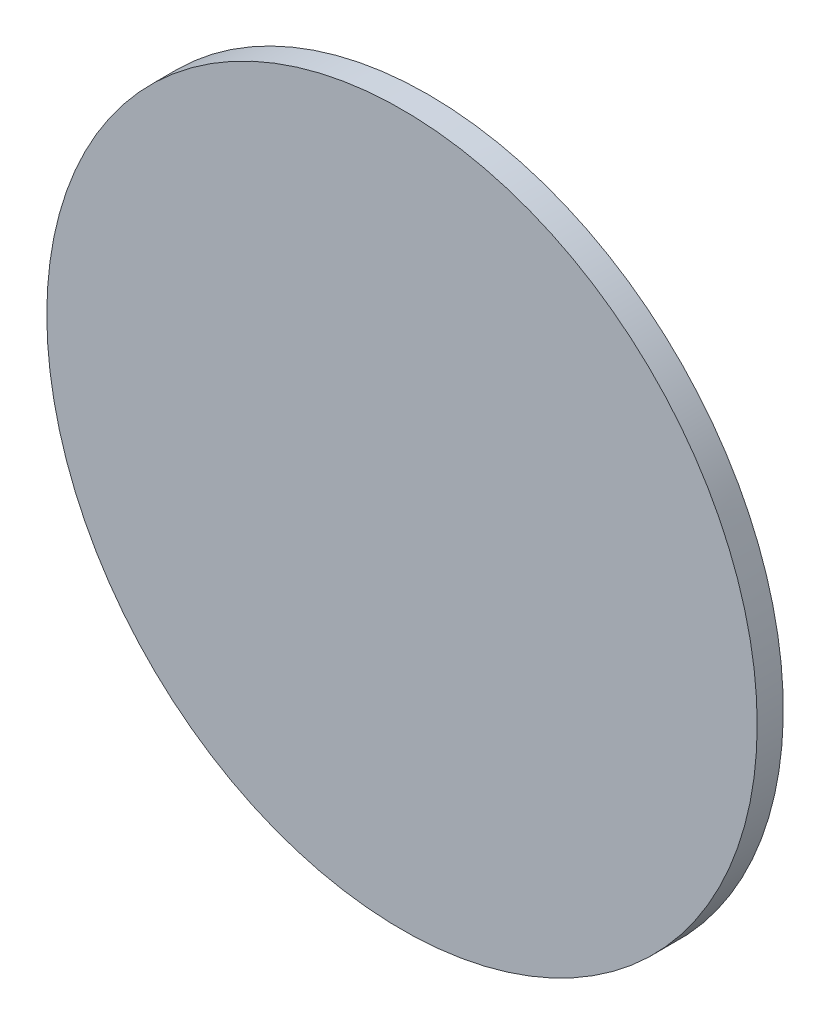
SolidWorks part; units mm, degrees
ref_plane "前视基准面" through (0, 0, 0) normal (0, 0, 1) x (1, 0, 0)
ref_plane "上视基准面" through (0, 0, 0) normal (0, 1, 0) x (1, 0, 0)
ref_plane "右视基准面" through (0, 0, 0) normal (1, 0, 0) x (0, 0, -1)
other "Configuration Table"
curve "曲线20"
  spline degree 3 poles (0, 0, 0) (0, 0.0067, 0.0001) (0, 0.02, 0.0004) (0, 0.04, 0.0008) (0, 0.06, 0.0012) (0, 0.08, 0.0016) (0, 0.1, 0.002) (0, 0.12, 0.0024) (0, 0.14, 0.0028) (0, 0.16, 0.0032) (0, 0.18, 0.0036) (0, 0.2, 0.004) (0, 0.22, 0.0044) (0, 0.24, 0.0048) (0, 0.26, 0.0052) (0, 0.28, 0.0056) (0, 0.3, 0.006) (0, 0.32, 0.0064) (0, 0.34, 0.0068) (0, 0.36, 0.0072) (0, 0.38, 0.0076) (0, 0.4, 0.008) (0, 0.42, 0.0084) (0, 0.44, 0.0088) (0, 0.46, 0.0092) (0, 0.48, 0.0096) (0, 0.5, 0.01) (0, 0.52, 0.0104) (0, 0.54, 0.0108) (0, 0.56, 0.0112) (0, 0.58, 0.0116) (0, 0.6, 0.012) (0, 0.62, 0.0124) (0, 0.64, 0.0128) (0, 0.66, 0.0132) (0, 0.68, 0.0136) (0, 0.7, 0.014) (0, 0.72, 0.0144) (0, 0.74, 0.0148) (0, 0.76, 0.0152) (0, 0.78, 0.0156) (0, 0.8, 0.016) (0, 0.82, 0.0164) (0, 0.84, 0.0168) (0, 0.86, 0.0172) (0, 0.88, 0.0176) (0, 0.9, 0.018) (0, 0.92, 0.0184) (0, 0.9399, 0.0187) (0, 0.9605, 0.0197) (0, 0.978, 0.0176) (0, 1.0024, 0.0258) (0, 1, 0.01) (0, 0.9976, -0.0059) (0, 1.022, 0.0033) (0, 1.0395, 0.0018) (0, 1.0601, 0.0038) (0, 1.08, 0.0048) (0, 1.1, 0.006) (0, 1.12, 0.0072) (0, 1.14, 0.0084) (0, 1.16, 0.0096) (0, 1.18, 0.0108) (0, 1.2, 0.012) (0, 1.22, 0.0132) (0, 1.24, 0.0144) (0, 1.26, 0.0156) (0, 1.28, 0.0168) (0, 1.3, 0.018) (0, 1.32, 0.0192) (0, 1.34, 0.0204) (0, 1.36, 0.0216) (0, 1.38, 0.0228) (0, 1.4, 0.024) (0, 1.42, 0.0253) (0, 1.44, 0.0265) (0, 1.46, 0.0277) (0, 1.48, 0.0289) (0, 1.5, 0.0301) (0, 1.52, 0.0313) (0, 1.54, 0.0325) (0, 1.56, 0.0337) (0, 1.58, 0.0349) (0, 1.6, 0.0361) (0, 1.62, 0.0373) (0, 1.64, 0.0385) (0, 1.66, 0.0397) (0, 1.68, 0.0409) (0, 1.7, 0.0421) (0, 1.72, 0.0433) (0, 1.74, 0.0445) (0, 1.76, 0.0457) (0, 1.78, 0.0469) (0, 1.8, 0.0481) (0, 1.82, 0.0493) (0, 1.84, 0.0505) (0, 1.86, 0.0517) (0, 1.88, 0.0529) (0, 1.9, 0.0541) (0, 1.92, 0.0553) (0, 1.9399, 0.0564) (0, 1.9604, 0.0582) (0, 1.9784, 0.0572) (0, 2.0059, 0.0664) (0, 1.998, 0.038) (0, 2.002, 0.0222) (0, 1.9941, -0.0065) (0, 2.0216, 0.0038) (0, 2.0396, 0.0036) (0, 2.0601, 0.0062) (0, 2.08, 0.008) (0, 2.1, 0.0101) (0, 2.12, 0.0121) (0, 2.14, 0.0141) (0, 2.16, 0.0161) (0, 2.18, 0.0181) (0, 2.2, 0.0201) (0, 2.22, 0.0221) (0, 2.24, 0.0241) (0, 2.26, 0.0261) (0, 2.28, 0.0281) (0, 2.3, 0.0302) (0, 2.32, 0.0322) (0, 2.34, 0.0342) (0, 2.36, 0.0362) (0, 2.38, 0.0382) (0, 2.4, 0.0402) (0, 2.42, 0.0422) (0, 2.44, 0.0442) (0, 2.46, 0.0462) (0, 2.48, 0.0483) (0, 2.5, 0.0503) (0, 2.52, 0.0523) (0, 2.54, 0.0543) (0, 2.56, 0.0563) (0, 2.58, 0.0583) (0, 2.6, 0.0603) (0, 2.62, 0.0623) (0, 2.64, 0.0643) (0, 2.66, 0.0663) (0, 2.68, 0.0684) (0, 2.7, 0.0704) (0, 2.72, 0.0724) (0, 2.74, 0.0744) (0, 2.76, 0.0764) (0, 2.78, 0.0784) (0, 2.8, 0.0804) (0, 2.82, 0.0824) (0, 2.84, 0.0844) (0, 2.86, 0.0865) (0, 2.88, 0.0885) (0, 2.9, 0.0905) (0, 2.92, 0.0925) (0, 2.9399, 0.0944) (0, 2.9604, 0.097) (0, 2.9785, 0.0968) (0, 3.0058, 0.1069) (0, 2.9984, 0.0787) (0, 3.0005, 0.0609) (0, 2.9995, 0.0396) (0, 3.0016, 0.0219) (0, 2.9942, -0.0067) (0, 3.0216, 0.0046) (0, 3.0396, 0.0052) (0, 3.0601, 0.0086) (0, 3.08, 0.0113) (0, 3.1, 0.0142) (0, 3.12, 0.017) (0, 3.14, 0.0198) (0, 3.16, 0.0226) (0, 3.18, 0.0255) (0, 3.2, 0.0283) (0, 3.22, 0.0311) (0, 3.24, 0.0339) (0, 3.26, 0.0368) (0, 3.28, 0.0396) (0, 3.3, 0.0424) (0, 3.32, 0.0453) (0, 3.34, 0.0481) (0, 3.36, 0.0509) (0, 3.38, 0.0537) (0, 3.4, 0.0566) (0, 3.42, 0.0594) (0, 3.44, 0.0622) (0, 3.46, 0.0651) (0, 3.48, 0.0679) (0, 3.5, 0.0707) (0, 3.52, 0.0735) (0, 3.54, 0.0764) (0, 3.56, 0.0792) (0, 3.58, 0.082) (0, 3.6, 0.0849) (0, 3.62, 0.0877) (0, 3.64, 0.0905) (0, 3.66, 0.0933) (0, 3.68, 0.0962) (0, 3.7, 0.099) (0, 3.72, 0.1018) (0, 3.74, 0.1047) (0, 3.76, 0.1075) (0, 3.78, 0.1103) (0, 3.8, 0.1131) (0, 3.82, 0.116) (0, 3.84, 0.1188) (0, 3.86, 0.1216) (0, 3.88, 0.1245) (0, 3.9, 0.1273) (0, 3.92, 0.1301) (0, 3.9399, 0.1328) (0, 3.9604, 0.1362) (0, 3.9785, 0.1368) (0, 4.0058, 0.1481) (0, 3.9985, 0.1194) (0, 4.0004, 0.1015) (0, 3.9999, 0.0806) (0, 4.0001, 0.0608) (0, 3.9996, 0.0399) (0, 4.0015, 0.022) (0, 3.9943, -0.0069) (0, 4.0216, 0.0055) (0, 4.0396, 0.0068) (0, 4.0601, 0.0111) (0, 4.08, 0.0146) (0, 4.1, 0.0183) (0, 4.12, 0.022) (0, 4.14, 0.0256) (0, 4.16, 0.0293) (0, 4.18, 0.0329) (0, 4.2, 0.0366) (0, 4.22, 0.0403) (0, 4.24, 0.0439) (0, 4.26, 0.0476) (0, 4.28, 0.0512) (0, 4.3, 0.0549) (0, 4.32, 0.0586) (0, 4.34, 0.0622) (0, 4.36, 0.0659) (0, 4.38, 0.0696) (0, 4.4, 0.0732) (0, 4.42, 0.0769) (0, 4.44, 0.0805) (0, 4.46, 0.0842) (0, 4.48, 0.0879) (0, 4.5, 0.0915) (0, 4.52, 0.0952) (0, 4.54, 0.0988) (0, 4.56, 0.1025) (0, 4.58, 0.1062) (0, 4.6, 0.1098) (0, 4.62, 0.1135) (0, 4.64, 0.1171) (0, 4.66, 0.1208) (0, 4.68, 0.1245) (0, 4.7, 0.1281) (0, 4.72, 0.1318) (0, 4.74, 0.1354) (0, 4.76, 0.1391) (0, 4.78, 0.1428) (0, 4.8, 0.1464) (0, 4.82, 0.1501) (0, 4.84, 0.1537) (0, 4.86, 0.1574) (0, 4.88, 0.1611) (0, 4.9, 0.1647) (0, 4.92, 0.1684) (0, 4.94, 0.172) (0, 4.96, 0.1757) (0, 4.98, 0.1794) (0, 4.9933, 0.1818) (0, 5, 0.183) knots 0 0 0 0 0.003735 0.00747 0.011205 0.01494 0.018675 0.022411 0.026146 0.029881 0.033616 0.037351 0.041086 0.044821 0.048556 0.052291 0.056026 0.059762 0.063497 0.067232 0.070967 0.074702 0.078437 0.082172 0.085907 0.089642 0.093377 0.097113 0.100848 0.104583 0.108318 0.112053 0.115788 0.119523 0.123258 0.126993 0.130728 0.134464 0.138199 0.141934 0.145669 0.149404 0.153139 0.156874 0.160609 0.164344 0.168079 0.171815 0.17555 0.179285 0.18302 0.186755 0.188623 0.190491 0.194232 0.197973 0.201714 0.205455 0.209196 0.212937 0.216678 0.22042 0.224161 0.227902 0.231643 0.235384 0.239125 0.242866 0.246607 0.250348 0.254089 0.257831 0.261572 0.265313 0.269054 0.272795 0.276536 0.280277 0.284018 0.287759 0.2915 0.295241 0.298983 0.302724 0.306465 0.310206 0.313947 0.317688 0.321429 0.32517 0.328911 0.332652 0.336393 0.340135 0.343876 0.347617 0.351358 0.355099 0.35884 0.362581 0.366322 0.370063 0.373804 0.377546 0.381287 0.385029 0.388771 0.392524 0.396277 0.40003 0.403784 0.407537 0.41129 0.415043 0.418796 0.42255 0.426303 0.430056 0.433809 0.437562 0.441315 0.445069 0.448822 0.452575 0.456328 0.460081 0.463834 0.467588 0.471341 0.475094 0.478847 0.4826 0.486353 0.490107 0.49386 0.497613 0.501366 0.505119 0.508873 0.512626 0.516379 0.520132 0.523885 0.527638 0.531392 0.535145 0.538898 0.542651 0.546404 0.550157 0.553911 0.557664 0.561417 0.56517 0.568923 0.572676 0.57643 0.580184 0.583937 0.587691 0.591445 0.595199 0.598971 0.602742 0.606514 0.610285 0.614057 0.617828 0.6216 0.625371 0.629143 0.632914 0.636686 0.640457 0.644229 0.648 0.651772 0.655543 0.659315 0.663086 0.666858 0.670629 0.674401 0.678172 0.681944 0.685715 0.689487 0.693258 0.69703 0.700802 0.704573 0.708345 0.712116 0.715888 0.719659 0.723431 0.727202 0.730974 0.734745 0.738517 0.742288 0.74606 0.749831 0.753603 0.757374 0.761146 0.764917 0.768689 0.77246 0.776232 0.780003 0.783775 0.787547 0.791319 0.795092 0.798864 0.802636 0.806408 0.810181 0.813977 0.817773 0.82157 0.825366 0.829163 0.832959 0.836755 0.840552 0.844348 0.848145 0.851941 0.855737 0.859534 0.86333 0.867126 0.870923 0.874719 0.878516 0.882312 0.886108 0.889905 0.893701 0.897498 0.901294 0.90509 0.908887 0.912683 0.91648 0.920276 0.924072 0.927869 0.931665 0.935461 0.939258 0.943054 0.946851 0.950647 0.954443 0.95824 0.962036 0.965833 0.969629 0.973425 0.977222 0.981018 0.984814 0.988611 0.992407 0.996204 1 1 1 1
sketch "草图2" plane through (0, 0, 0) normal (1, 0, 0) x (0, 0, -1)
  line L0 (0, 0) -> (-2.238, 0) construction
  line L2 (0, 0) -> (-0.5501, 0)
  line L3 (-0.5501, 0) -> (-0.5501, 5)
  line L4 (-0.5501, 5) -> (-0.183, 5)
  spline S0 degree 3 poles (1998.7905, -46.854) (0.6978, -57.8992) (0.5787, -28.9283) (-0.0048, 0.24) (-0.0099, 0.4933) (-0.0152, 0.76) (-0.0165, 0.8267) (-0.0172, 0.86) (-0.0176, 0.88) (-0.018, 0.9) (-0.0184, 0.92) (-0.0187, 0.9399) (-0.0197, 0.9605) (-0.0176, 0.978) (-0.0258, 1.0024) (-0.01, 1) (0.0059, 0.9976) (-0.0033, 1.022) (-0.0018, 1.0395) (-0.0038, 1.0601) (-0.0048, 1.08) (-0.006, 1.1) (-0.0072, 1.12) (-0.0096, 1.16) (-0.0128, 1.2133) (-0.0172, 1.2867) (-0.0216, 1.36) (-0.0261, 1.4333) (-0.0305, 1.5067) (-0.0349, 1.58) (-0.0393, 1.6533) (-0.0437, 1.7267) (-0.0473, 1.7867) (-0.0501, 1.8333) (-0.0517, 1.86) (-0.0529, 1.88) (-0.0541, 1.9) (-0.0553, 1.92) (-0.0564, 1.9399) (-0.0582, 1.9604) (-0.0572, 1.9784) (-0.0664, 2.0059) (-0.038, 1.998) (-0.0222, 2.002) (0.0065, 1.9941) (-0.0038, 2.0216) (-0.0036, 2.0396) (-0.0062, 2.0601) (-0.008, 2.08) (-0.0101, 2.1) (-0.0127, 2.1267) (-0.0168, 2.1667) (-0.0221, 2.22) (-0.0282, 2.28) (-0.0342, 2.34) (-0.0402, 2.4) (-0.0462, 2.46) (-0.0523, 2.52) (-0.0583, 2.58) (-0.065, 2.6467) (-0.0717, 2.7133) (-0.0784, 2.78) (-0.0831, 2.8267) (-0.0865, 2.86) (-0.0885, 2.88) (-0.0905, 2.9) (-0.0925, 2.92) (-0.0944, 2.9399) (-0.097, 2.9604) (-0.0968, 2.9785) (-0.1069, 3.0058) (-0.0787, 2.9984) (-0.0609, 3.0005) (-0.0396, 2.9995) (-0.0219, 3.0016) (0.0067, 2.9942) (-0.0046, 3.0216) (-0.0052, 3.0396) (-0.0086, 3.0601) (-0.0113, 3.08) (-0.0142, 3.1) (-0.0179, 3.1267) (-0.0226, 3.16) (-0.0292, 3.2067) (-0.0377, 3.2667) (-0.0471, 3.3333) (-0.0566, 3.4) (-0.066, 3.4667) (-0.0754, 3.5333) (-0.0858, 3.6067) (-0.0952, 3.6733) (-0.1056, 3.7467) (-0.1141, 3.8067) (-0.1207, 3.8533) (-0.1245, 3.88) (-0.1273, 3.9) (-0.1301, 3.92) (-0.1328, 3.9399) (-0.1362, 3.9604) (-0.1368, 3.9785) (-0.1481, 4.0058) (-0.1194, 3.9985) (-0.1015, 4.0004) (-0.0806, 3.9999) (-0.0608, 4.0001) (-0.0399, 3.9996) (-0.022, 4.0015) (0.0069, 3.9943) (-0.0055, 4.0216) (-0.0068, 4.0396) (-0.0111, 4.0601) (-0.0146, 4.08) (-0.0183, 4.1) (-0.022, 4.12) (-0.0293, 4.16) (-0.039, 4.2133) (-0.0525, 4.2867) (-0.0647, 4.3533) (-0.0781, 4.4267) (-0.0903, 4.4933) (-0.1025, 4.56) (-0.1147, 4.6267) (-0.1269, 4.6933) (-0.1391, 4.76) (-0.1513, 4.8267) (-0.1635, 4.8933) (-0.1733, 4.9467) (-2.3397, 16.7879) (-5.6155, 28.4054) (1960.1782, 400.405) knots -16.21873 -16.21873 -16.21873 -16.21873 0.003735 0.00747 0.123258 0.145669 0.156874 0.160609 0.164344 0.168079 0.171815 0.17555 0.179285 0.18302 0.186755 0.188623 0.190491 0.194232 0.197973 0.201714 0.205455 0.209196 0.212937 0.216678 0.231643 0.242866 0.257831 0.272795 0.284018 0.298983 0.313947 0.32517 0.340135 0.347617 0.351358 0.355099 0.35884 0.362581 0.366322 0.370063 0.373804 0.377546 0.381287 0.385029 0.388771 0.392524 0.396277 0.40003 0.403784 0.407537 0.41129 0.418796 0.430056 0.441315 0.452575 0.463834 0.475094 0.486353 0.497613 0.508873 0.523885 0.535145 0.546404 0.550157 0.553911 0.557664 0.561417 0.56517 0.568923 0.572676 0.57643 0.580184 0.583937 0.587691 0.591445 0.595199 0.598971 0.602742 0.606514 0.610285 0.614057 0.617828 0.625371 0.632914 0.644229 0.659315 0.670629 0.681944 0.69703 0.708345 0.723431 0.734745 0.749831 0.757374 0.761146 0.764917 0.768689 0.77246 0.776232 0.780003 0.783775 0.787547 0.791319 0.795092 0.798864 0.802636 0.806408 0.810181 0.813977 0.817773 0.82157 0.825366 0.829163 0.832959 0.836755 0.851941 0.86333 0.878516 0.889905 0.90509 0.91648 0.927869 0.943054 0.954443 0.965833 0.981018 0.992407 0.996204 7.724012 7.724012 7.724012 7.724012 only from (0, 0) to (-0.183, 5) construction
  spline S1 degree 3 poles (0, 0) (-0.0012, 0.06) (-0.0031, 0.1533) (-0.0083, 0.4133) (-0.0127, 0.6333) (-0.0165, 0.8267) (-0.0172, 0.86) (-0.0176, 0.88) (-0.018, 0.9) (-0.0184, 0.92) (-0.0187, 0.9399) (-0.0197, 0.9605) (-0.0176, 0.978) (-0.0258, 1.0024) (-0.01, 1) (0.0059, 0.9976) (-0.0033, 1.022) (-0.0018, 1.0395) (-0.0038, 1.0601) (-0.0048, 1.08) (-0.006, 1.1) (-0.0072, 1.12) (-0.0096, 1.16) (-0.0128, 1.2133) (-0.0172, 1.2867) (-0.0216, 1.36) (-0.0261, 1.4333) (-0.0305, 1.5067) (-0.0349, 1.58) (-0.0393, 1.6533) (-0.0437, 1.7267) (-0.0473, 1.7867) (-0.0501, 1.8333) (-0.0517, 1.86) (-0.0529, 1.88) (-0.0541, 1.9) (-0.0553, 1.92) (-0.0564, 1.9399) (-0.0582, 1.9604) (-0.0572, 1.9784) (-0.0664, 2.0059) (-0.038, 1.998) (-0.0222, 2.002) (0.0065, 1.9941) (-0.0038, 2.0216) (-0.0036, 2.0396) (-0.0062, 2.0601) (-0.008, 2.08) (-0.0101, 2.1) (-0.0127, 2.1267) (-0.0168, 2.1667) (-0.0221, 2.22) (-0.0282, 2.28) (-0.0342, 2.34) (-0.0402, 2.4) (-0.0462, 2.46) (-0.0523, 2.52) (-0.0583, 2.58) (-0.065, 2.6467) (-0.0717, 2.7133) (-0.0784, 2.78) (-0.0831, 2.8267) (-0.0865, 2.86) (-0.0885, 2.88) (-0.0905, 2.9) (-0.0925, 2.92) (-0.0944, 2.9399) (-0.097, 2.9604) (-0.0968, 2.9785) (-0.1069, 3.0058) (-0.0787, 2.9984) (-0.0609, 3.0005) (-0.0396, 2.9995) (-0.0219, 3.0016) (0.0067, 2.9942) (-0.0046, 3.0216) (-0.0052, 3.0396) (-0.0086, 3.0601) (-0.0113, 3.08) (-0.0142, 3.1) (-0.0179, 3.1267) (-0.0226, 3.16) (-0.0292, 3.2067) (-0.0377, 3.2667) (-0.0471, 3.3333) (-0.0566, 3.4) (-0.066, 3.4667) (-0.0754, 3.5333) (-0.0858, 3.6067) (-0.0952, 3.6733) (-0.1056, 3.7467) (-0.1141, 3.8067) (-0.1207, 3.8533) (-0.1245, 3.88) (-0.1273, 3.9) (-0.1301, 3.92) (-0.1328, 3.9399) (-0.1362, 3.9604) (-0.1368, 3.9785) (-0.1481, 4.0058) (-0.1194, 3.9985) (-0.1015, 4.0004) (-0.0806, 3.9999) (-0.0608, 4.0001) (-0.0399, 3.9996) (-0.022, 4.0015) (0.0069, 3.9943) (-0.0055, 4.0216) (-0.0068, 4.0396) (-0.0111, 4.0601) (-0.0146, 4.08) (-0.0183, 4.1) (-0.022, 4.12) (-0.0293, 4.16) (-0.039, 4.2133) (-0.0525, 4.2867) (-0.0647, 4.3533) (-0.0781, 4.4267) (-0.0903, 4.4933) (-0.1025, 4.56) (-0.1147, 4.6267) (-0.1269, 4.6933) (-0.1391, 4.76) (-0.1513, 4.8267) (-0.1635, 4.8933) (-0.1745, 4.9533) (-0.1806, 4.9867) (-0.183, 5) knots 0 0 0 0 0.033616 0.052291 0.145669 0.156874 0.160609 0.164344 0.168079 0.171815 0.17555 0.179285 0.18302 0.186755 0.188623 0.190491 0.194232 0.197973 0.201714 0.205455 0.209196 0.212937 0.216678 0.231643 0.242866 0.257831 0.272795 0.284018 0.298983 0.313947 0.32517 0.340135 0.347617 0.351358 0.355099 0.35884 0.362581 0.366322 0.370063 0.373804 0.377546 0.381287 0.385029 0.388771 0.392524 0.396277 0.40003 0.403784 0.407537 0.41129 0.418796 0.430056 0.441315 0.452575 0.463834 0.475094 0.486353 0.497613 0.508873 0.523885 0.535145 0.546404 0.550157 0.553911 0.557664 0.561417 0.56517 0.568923 0.572676 0.57643 0.580184 0.583937 0.587691 0.591445 0.595199 0.598971 0.602742 0.606514 0.610285 0.614057 0.617828 0.625371 0.632914 0.644229 0.659315 0.670629 0.681944 0.69703 0.708345 0.723431 0.734745 0.749831 0.757374 0.761146 0.764917 0.768689 0.77246 0.776232 0.780003 0.783775 0.787547 0.791319 0.795092 0.798864 0.802636 0.806408 0.810181 0.813977 0.817773 0.82157 0.825366 0.829163 0.832959 0.836755 0.851941 0.86333 0.878516 0.889905 0.90509 0.91648 0.927869 0.943054 0.954443 0.965833 0.981018 0.992407 1 1 1 1
revolve "旋转6" add sketch "草图2" angle 360 about L0
